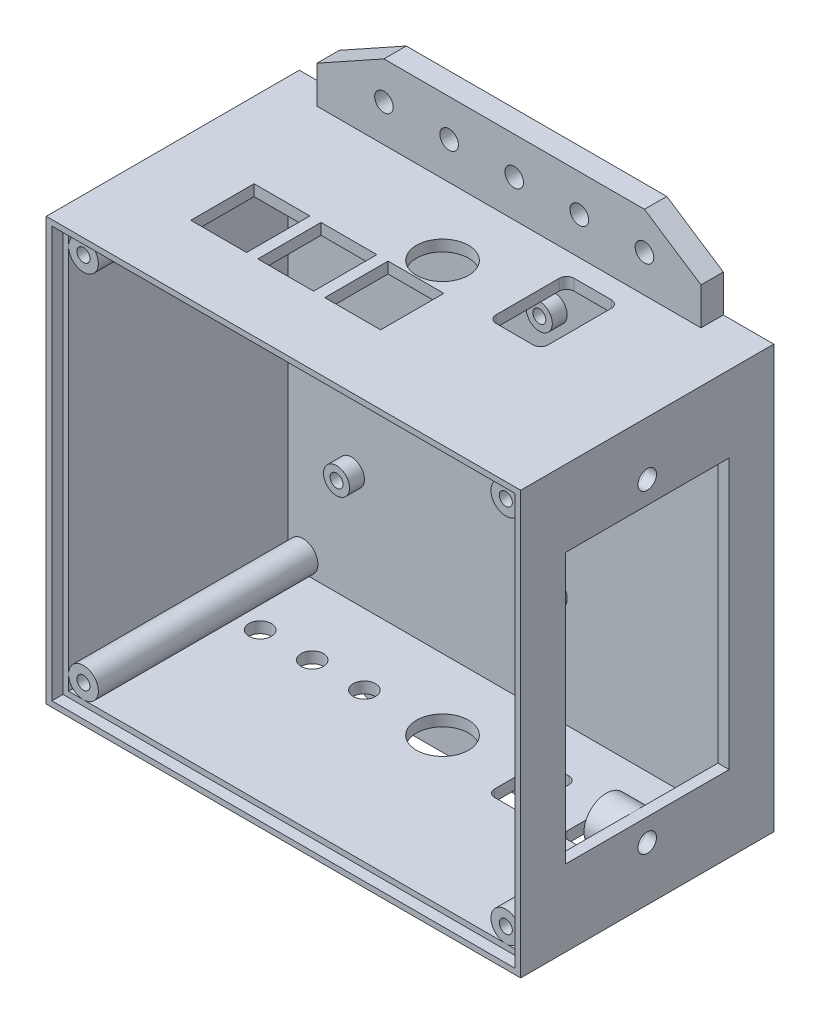
SolidWorks part; units mm, degrees
ref_plane "Alzado" through (0, 0, 0) normal (0, 0, 1) x (1, 0, 0)
ref_plane "Planta" through (0, 0, 0) normal (0, 1, 0) x (1, 0, 0)
ref_plane "Vista lateral" through (0, 0, 0) normal (1, 0, 0) x (0, 0, -1)
sketch "Croquis1" plane through (0, 0, 0) normal (0, 0, 1) x (1, 0, 0)
  line L0 (-74.48, 81) -> (53, 81)
  line L1 (-74.48, 81) -> (-74.48, -24.5)
  line L4 (53, 81) -> (53, -24.5)
  line L6 (53, -24.5) -> (53, -32.5)
  line L7 (53, -32.5) -> (-74.48, -32.5)
  line L8 (-74.48, -24.5) -> (-74.48, -32.5)
  circle A0 centre (0, 0) radius 1.75
  circle A1 centre (0, 66) radius 1.75
  circle A2 centre (-54.48, 0.5) radius 1.75
extrude "Saliente-Extruir1" add sketch "Croquis1" along normal blind 6
sketch "Croquis2" plane through (0, 0, 0) normal (0, 0, 1) x (1, 0, 0)
  circle A0 centre (-54.48, 0.5) radius 1.75
  circle A1 centre (-54.48, 0.5) radius 3.5
  circle A2 centre (0, 0) radius 3.5
  circle A3 centre (0, 0) radius 1.75
  circle A4 centre (0, 66) radius 1.75
  circle A5 centre (0, 66) radius 3.5
extrude "Saliente-Extruir2" add sketch "Croquis2" along normal blind 10
sketch "Croquis3" plane through (0, 0, 0) normal (0, 0, 1) x (1, 0, 0)
  circle A0 centre (0, 66) radius 3.5
  circle A1 centre (0, 66) radius 1.75
  circle A2 centre (0, 0) radius 1.75
  circle A3 centre (0, 0) radius 3.5
  circle A4 centre (-54.48, 0.5) radius 1.75
  circle A5 centre (-54.48, 0.5) radius 3.5
extrude "Cortar-Extruir1" cut sketch "Croquis3" along normal blind 3
sketch "Croquis4" plane through (0, 0, 0) normal (0, 0, 1) x (1, 0, 0)
  line L0 (53, 81) -> (-74.48, 81)
  line L1 (-74.48, 81) -> (-74.48, -24.5)
  line L2 (-74.48, -24.5) -> (-74.48, -32.5)
  line L3 (53, 81) -> (53, -32.5)
  line L5 (-74.48, -32.5) -> (53, -32.5)
  line L6 (-71.48, -21.5) -> (-71.48, -29.5)
  line L7 (-71.48, -29.5) -> (50, -29.5)
  line L8 (50, -29.5) -> (50, -21.5)
  line L13 (-71.48, 78) -> (50, 78)
  line L14 (-71.48, 78) -> (-71.48, -21.5)
  line L16 (50, 78) -> (50, -21.5)
  circle A0 centre (-67.48, -25.5) radius 1.75
  circle A1 centre (-67.48, -25.5) radius 4
  circle A2 centre (-67.48, 74) radius 1.75
  circle A3 centre (-67.48, 74) radius 4
  circle A4 centre (46, -25.5) radius 4
  circle A5 centre (46, -25.5) radius 1.75
  circle A6 centre (46, 74) radius 4
  circle A7 centre (46, 74) radius 1.75
ref_plane "Plano1" through (55, 0, 0) normal (1, 0, 0) x (0, 0, -1)
extrude "Saliente-Extruir9" add sketch "Croquis4" along normal blind 68 separate body
sketch "Croquis6" plane through (55, 0, 0) normal (1, 0, 0) x (0, 0, -1)
  line L3 (-68, 81) -> (-68, -32.5) construction
  line L4 (-12, 60.5) -> (-56, 60.5)
  line L5 (-12, 60.5) -> (-12, -12)
  line L6 (-12, -12) -> (-56, -12)
  line L7 (-56, 60.5) -> (-56, -12)
  line L8 (-68, -32.5) -> (0, -32.5) construction
  line L9 (-68, -32.5) -> (0, -32.5) construction
  circle A0 centre (-34, 66.5) radius 2.5
  circle A1 centre (-34, -18) radius 2.5
extrude "Cortar-Extruir2" cut sketch "Croquis6" against normal blind 5
ref_plane "Plano2" through (50, 0, 0) normal (1, 0, 0) x (0, 0, -1)
sketch "Croquis7" plane through (50, 0, 0) normal (1, 0, 0) x (0, 0, -1)
  circle A0 centre (-34, 66.5) radius 2.5
  circle A1 centre (-34, 66.5) radius 6
  circle A2 centre (-34, -18) radius 2.5
  circle A3 centre (-34, -18) radius 6
extrude "Saliente-Extruir10" add sketch "Croquis7" against normal blind 8
sketch "Croquis8" plane through (0, 0, 0) normal (0, 1, 0) x (1, 0, 0)
  circle A0 centre (-11, -25) radius 7
extrude "Cortar-Extruir3" cut sketch "Croquis8" against normal blind 42 and the other way blind 101
sketch "Croquis9" plane through (0, 0, 0) normal (0, 1, 0) x (1, 0, 0)
  line L2 (35, -32.5) -> (30, -32.5)
  line L3 (37, -30.5) -> (37, -19.5)
  line L4 (15.5, -32.5) -> (10.5, -32.5)
  line L5 (17.5, -30.5) -> (17.5, -19.5)
  line L6 (15.5, -17.5) -> (10.5, -17.5)
  line L7 (8.5, -30.5) -> (8.5, -19.5)
  line L8 (35, -17.5) -> (30, -17.5)
  line L9 (28, -30.5) -> (28, -19.5)
  arc A0 (8.5, -19.5) -> (10.5, -17.5) centre (10.5, -19.5) cw
  arc A1 (15.5, -17.5) -> (17.5, -19.5) centre (15.5, -19.5) cw
  arc A2 (17.5, -30.5) -> (15.5, -32.5) centre (15.5, -30.5) cw
  arc A3 (10.5, -32.5) -> (8.5, -30.5) centre (10.5, -30.5) cw
  arc A4 (28, -19.5) -> (30, -17.5) centre (30, -19.5) cw
  arc A5 (35, -17.5) -> (37, -19.5) centre (35, -19.5) cw
  arc A6 (37, -30.5) -> (35, -32.5) centre (35, -30.5) cw
  arc A7 (30, -32.5) -> (28, -30.5) centre (30, -30.5) cw
  circle A10 centre (-60, -25) radius 3
  circle A11 centre (-46, -25) radius 3
  circle A12 centre (-32, -25) radius 3
extrude "Cortar-Extruir4" cut sketch "Croquis9" against normal blind 42
ref_plane "Plano3" through (0, 81, 0) normal (0, 1, 0) x (1, 0, 0)
sketch "Croquis10" plane through (0, 81, 0) normal (0, 1, 0) x (1, 0, 0)
  line L2 (10.86, -32.5) -> (20.86, -32.5)
  line L3 (8.86, -30.5) -> (8.86, -13.5)
  line L4 (10.86, -11.5) -> (20.86, -11.5)
  line L5 (-18.14, -49.5) -> (-3.14, -49.5)
  line L6 (-18.14, -49.5) -> (-18.14, -32.5)
  line L7 (-18.14, -32.5) -> (-3.14, -32.5)
  line L8 (22.86, -30.5) -> (22.86, -13.5)
  line L9 (-3.14, -49.5) -> (-3.14, -32.5)
  line L12 (-36.14, -49.5) -> (-21.14, -49.5)
  line L14 (-36.14, -49.5) -> (-36.14, -32.5)
  line L15 (-36.14, -32.5) -> (-21.14, -32.5)
  line L16 (-21.14, -49.5) -> (-21.14, -32.5)
  line L19 (-54.14, -49.5) -> (-39.14, -49.5)
  line L20 (-54.14, -49.5) -> (-54.14, -32.5)
  line L21 (-54.14, -32.5) -> (-39.14, -32.5)
  line L22 (-39.14, -49.5) -> (-39.14, -32.5)
  arc A0 (20.86, -11.5) -> (22.86, -13.5) centre (20.86, -13.5) cw
  arc A1 (10.86, -11.5) -> (8.86, -13.5) centre (10.86, -13.5) ccw
  arc A2 (10.86, -32.5) -> (8.86, -30.5) centre (10.86, -30.5) cw
  arc A3 (20.86, -32.5) -> (22.86, -30.5) centre (20.86, -30.5) ccw
extrude "Cortar-Extruir5" cut sketch "Croquis10" against normal blind 22
ref_plane "Plano4" through (0, 0, 68) normal (0, 0, 1) x (1, 0, 0)
sketch "Croquis11" plane through (0, 0, 68) normal (0, 0, 1) x (1, 0, 0)
  line L9 (-72.98, 79.5) -> (51.5, 79.5)
  line L10 (-72.98, 79.5) -> (-72.98, -31)
  line L11 (-72.98, -31) -> (51.5, -31)
  line L12 (51.5, 79.5) -> (51.5, -31)
extrude "Cortar-Extruir6" cut sketch "Croquis11" against normal blind 3
sketch "Croquis12" plane through (0, 0, 0) normal (0, 0, 1) x (1, 0, 0)
  line L0 (-63.74, 81) -> (39.4481, 81)
  line L1 (-63.74, 91) -> (-45.74, 101)
  line L2 (-45.74, 101) -> (24.26, 101)
  line L4 (-74.48, -32.5) -> (53.4933, -32.5) construction
  line L5 (-45.74, -52.5) -> (24.26, -52.5)
  line L7 (24.26, -52.5) -> (39.4481, -42.5)
  line L8 (24.26, 101) -> (39.4481, 91)
  line L9 (39.4481, 91) -> (39.4481, 81)
  line L10 (-63.74, 91) -> (-63.74, 81)
  line L11 (39.4481, -42.5) -> (39.4481, -32.5)
  line L12 (39.4481, -32.5) -> (-63.74, -32.5)
  line L13 (-63.74, -32.5) -> (-63.74, -42.5)
  line L14 (-63.74, -42.5) -> (-45.74, -52.5)
  circle A0 centre (-10.74, 91) radius 2.5
  circle A1 centre (-45.74, 91) radius 2.5
  circle A2 centre (24.26, 91) radius 2.5
  circle A3 centre (-28.24, 91) radius 2.5
  circle A4 centre (6.76, 91) radius 2.5
  circle A5 centre (-10.74, -42.5) radius 2.5
  circle A6 centre (-45.74, -42.5) radius 2.5
  circle A7 centre (24.26, -42.5) radius 2.5
  circle A8 centre (-28.24, -42.5) radius 2.5
  circle A9 centre (6.76, -42.5) radius 2.5
  dimension "D1" = 70
  dimension "D2" = 103.1881
  dimension "D3" = 20
  dimension "D4" = 113.5
  dimension "D5" = 20
  dimension "D6" = 10
  dimension "D7" = 127.9733
  dimension "D8" = 153.5
extrude "Saliente-Extruir11" add sketch "Croquis12" along normal blind 6
